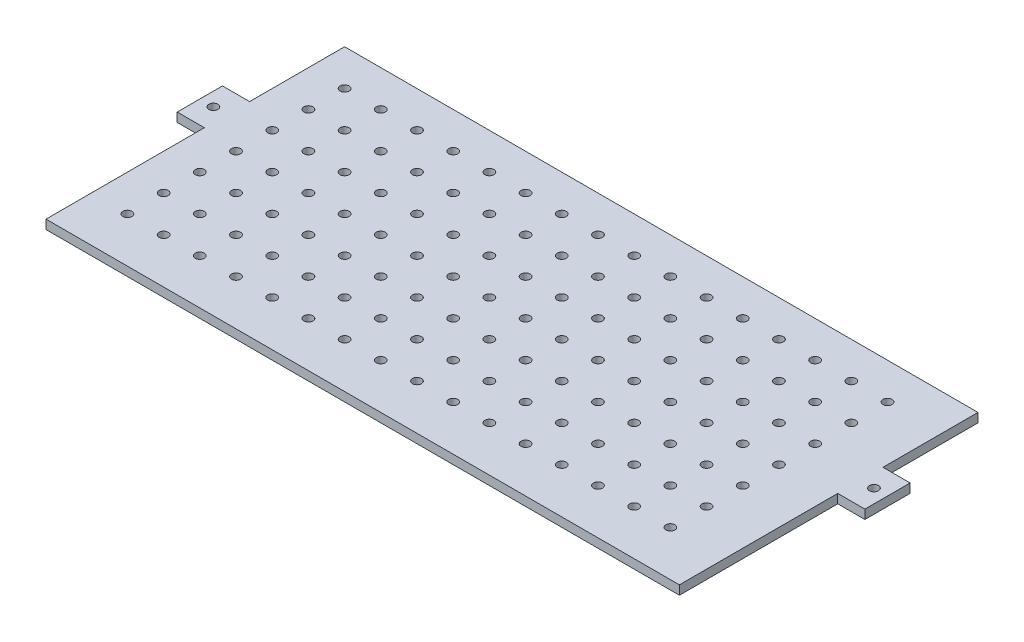
SolidWorks part; units mm, degrees
ref_plane "Alzado" through (0, 0, 0) normal (0, 0, 1) x (1, 0, 0)
ref_plane "Planta" through (0, 0, 0) normal (0, 1, 0) x (1, 0, 0)
ref_plane "Vista lateral" through (0, 0, 0) normal (1, 0, 0) x (0, 0, -1)
sketch "Croquis3" plane through (0, 0, 0) normal (0, 1, 0) x (1, 0, 0)
  line L1 (-350, -150) -> (350, -150)
  line L2 (-350, -150) -> (-350, 150)
  line L3 (-350, 150) -> (350, 150)
  line L4 (350, -150) -> (350, 150)
  line L5 (-350, -150) -> (350, 150) construction
  line L6 (-350, 150) -> (350, -150) construction
  line L7 (-380, -5) -> (-350, -5)
  line L8 (-380, -5) -> (-380, 45)
  line L9 (-380, 45) -> (-350, 45)
  line L10 (-350, -5) -> (-350, 45)
  line L11 (-380, -5) -> (-350, 45) construction
  line L12 (-380, 45) -> (-350, -5) construction
  line L13 (380, -5) -> (350, -5)
  line L14 (380, -5) -> (380, 45)
  line L15 (380, 45) -> (350, 45)
  line L16 (350, -5) -> (350, 45)
  line L17 (380, -5) -> (350, 45) construction
  line L18 (380, 45) -> (350, -5) construction
  line L19 (-350, -180) -> (350, -180)
  line L20 (-350, -180) -> (-350, -150)
  line L21 (-350, -150) -> (350, -150)
  line L22 (350, -180) -> (350, -150)
  line L23 (-350, -180) -> (350, -150) construction
  line L24 (-350, -150) -> (350, -180) construction
  point P0 (0, 0)
  point P6 (-365, 20)
  point P11 (365, 20)
  point P16 (0, -165)
  dimension "D1" = 700
  dimension "D2" = 300
  dimension "D3" = 30
  dimension "D4" = 50
  dimension "D5" = 30
  dimension "D6" = 50
  dimension "D7" = 700
  dimension "D8" = 30
  dimension "D9" = 130
  dimension "D10" = 130
extrude "Saliente-Extruir1" add sketch "Croquis3" along normal blind 10 contours L1 L4 L3 L2 | L19 L22 L1 L20 | L14 L15 L4 L13 | L9 L8 L7 L2
sketch "Croquis5" plane through (0, 10, 0) normal (0, 1, 0) x (1, 0, 0)
  line L0 (-350, 150) -> (350, 150) construction
  line L1 (-350, 45) -> (-350, 150) construction
  circle A0 centre (-310, 110) radius 5
  dimension "D1" = 40
  dimension "D2" = 40
extrude "Cortar-Extruir1" cut sketch "Croquis5" against normal up to surface (10 mm away) up to face at (0, 0, -8.3333)
pattern_linear "MatrizL1" count 16 spacing 40 along (1, 0, 0) count 7 spacing 40 along (0, 0, 1) of "Cortar-Extruir1"
sketch "Croquis6" plane through (0, 10, 0) normal (0, 1, 0) x (1, 0, 0)
  line L0 (-380, 45) -> (-350, 45) construction
  line L2 (380, 45) -> (350, 45) construction
  circle A0 centre (-365, 20) radius 5
  circle A1 centre (365, 20) radius 5
  point P4 (-365, 45)
  point P9 (365, 45)
  dimension "D1" = 25
  dimension "D2" = 25
extrude "Cortar-Extruir2" cut sketch "Croquis6" against normal up to surface (10 mm away) up to face at (290, 0, 135)
